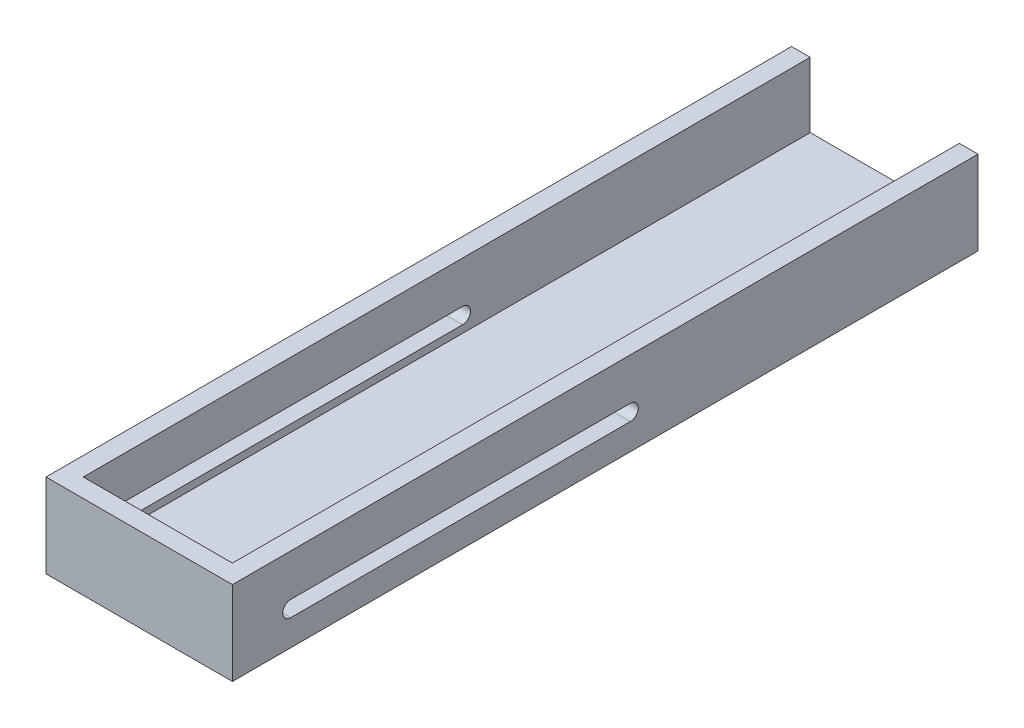
SolidWorks part; units mm, degrees
ref_plane "Front Plane" through (0, 0, 0) normal (0, 0, 1) x (1, 0, 0)
ref_plane "Top Plane" through (0, 0, 0) normal (0, 1, 0) x (1, 0, 0)
ref_plane "Right Plane" through (0, 0, 0) normal (1, 0, 0) x (0, 0, -1)
sketch "Sketch1" plane through (0, 0, 0) normal (0, 1, 0) x (1, 0, 0)
  line L1 (-25, -100) -> (25, -100)
  line L2 (-25, -100) -> (-25, 100)
  line L3 (-25, 100) -> (25, 100)
  line L4 (25, -100) -> (25, 100)
  line L5 (-25, -100) -> (25, 100) construction
  line L6 (-25, 100) -> (25, -100) construction
  point P0 (0, 0)
extrude "Boss-Extrude1" add sketch "Sketch1" along normal blind 20
sketch "Sketch2" plane through (0, 0, -100) normal (0, 0, -1) x (-1, 0, 0)
  line L0 (-25, 20) -> (25, 20) construction
  line L1 (-20, 37.5) -> (20, 37.5)
  line L2 (-20, 37.5) -> (-20, 2.5)
  line L3 (-20, 2.5) -> (20, 2.5)
  line L4 (20, 37.5) -> (20, 2.5)
  line L5 (-20, 37.5) -> (20, 2.5) construction
  line L6 (-20, 2.5) -> (20, 37.5) construction
  point P0 (0, 20)
extrude "Cut-Extrude1" cut sketch "Sketch2" against normal blind 190
sketch "Sketch3" plane through (0, 0, 90) normal (0, 0, -1) x (-1, 0, 0)
  line L1 (-20, 2.5) -> (20, 2.5)
  line L2 (-20, 2.5) -> (-20, 20)
  line L3 (-20, 20) -> (20, 20)
  line L4 (20, 2.5) -> (20, 20)
extrude "Cut-Extrude2" cut sketch "Sketch3" against normal blind 5
sketch "Sketch4" plane through (0, 0, -100) normal (0, 0, -1) x (-1, 0, 0)
  line L2 (-25, 0) -> (25, 0)
  line L3 (-25, 0) -> (-25, -2.5)
  line L4 (-25, -2.5) -> (25, -2.5)
  line L5 (25, 0) -> (25, -2.5)
extrude "Boss-Extrude2" add sketch "Sketch4" against normal blind 200
sketch "Sketch6" plane through (-25, 0, 0) normal (-1, 0, 0) x (0, 0, 1)
  line L3 (90.75, 4.5) -> (-95.75, 4.5)
  line L5 (90.75, 8.75) -> (-95.75, 8.75)
  arc A2 (90.75, 4.5) -> (90.75, 8.75) centre (90.75, 6.625) ccw
  arc A5 (-95.75, 8.75) -> (-95.75, 4.5) centre (-95.75, 6.625) ccw
extrude "Cut-Extrude4" cut sketch "Sketch6" against normal blind 200
sketch "Sketch14" plane through (-25, 0, 0) normal (-1, 0, 0) x (0, 0, 1)
  line L3 (-100, 20) -> (-100, -2.5) construction
  line L4 (-0.375, 4.5) -> (-100, 4.5)
  line L6 (-0.375, 8.75) -> (-100, 8.75)
  line L7 (-100, 4.5) -> (-100, 8.75)
  arc A1 (-0.375, 8.75) -> (-0.375, 4.5) centre (-0.375, 6.625) ccw
extrude "Boss-Extrude3" add sketch "Sketch14" against normal blind 50
sketch "Sketch15" plane through (0, 0, -100) normal (0, 0, -1) x (-1, 0, 0)
  line L1 (-20, 4.5) -> (20, 4.5)
  line L2 (-20, 4.5) -> (-20, 8.75)
  line L3 (-20, 8.75) -> (20, 8.75)
  line L4 (20, 4.5) -> (20, 8.75)
extrude "Cut-Extrude5" cut sketch "Sketch15" against normal blind 104
sketch "Sketch17" plane through (-25, 0, 0) normal (-1, 0, 0) x (0, 0, 1)
  line L0 (-0.375, 8.75) -> (-0.375, 4.5)
  line L1 (-6.75, 4.5) -> (-0.375, 4.5)
  line L3 (-6.75, 8.75) -> (-0.375, 8.75)
  arc A3 (-6.75, 8.75) -> (-6.75, 4.5) centre (-6.75, 6.625) ccw
extrude "Cut-Extrude6" cut sketch "Sketch17" against normal blind 104
sketch "Sketch18" plane through (-25, 0, 0) normal (-1, 0, 0) x (0, 0, 1)
  line L1 (84.375, 4.5) -> (90.75, 4.5)
  line L3 (84.375, 8.75) -> (90.75, 8.75)
  arc A0 (90.75, 4.5) -> (90.75, 8.75) centre (90.75, 6.625) ccw
  arc A3 (84.375, 4.5) -> (84.375, 8.75) centre (84.375, 6.625) ccw
extrude "Boss-Extrude4" add sketch "Sketch18" against normal blind 50
sketch "Sketch19" plane through (0, 0, 95) normal (0, 0, -1) x (-1, 0, 0)
  line L1 (-20, 4.5) -> (20, 4.5)
  line L2 (-20, 4.5) -> (-20, 8.75)
  line L3 (-20, 8.75) -> (20, 8.75)
  line L4 (20, 4.5) -> (20, 8.75)
extrude "Cut-Extrude7" cut sketch "Sketch19" along normal blind 50
